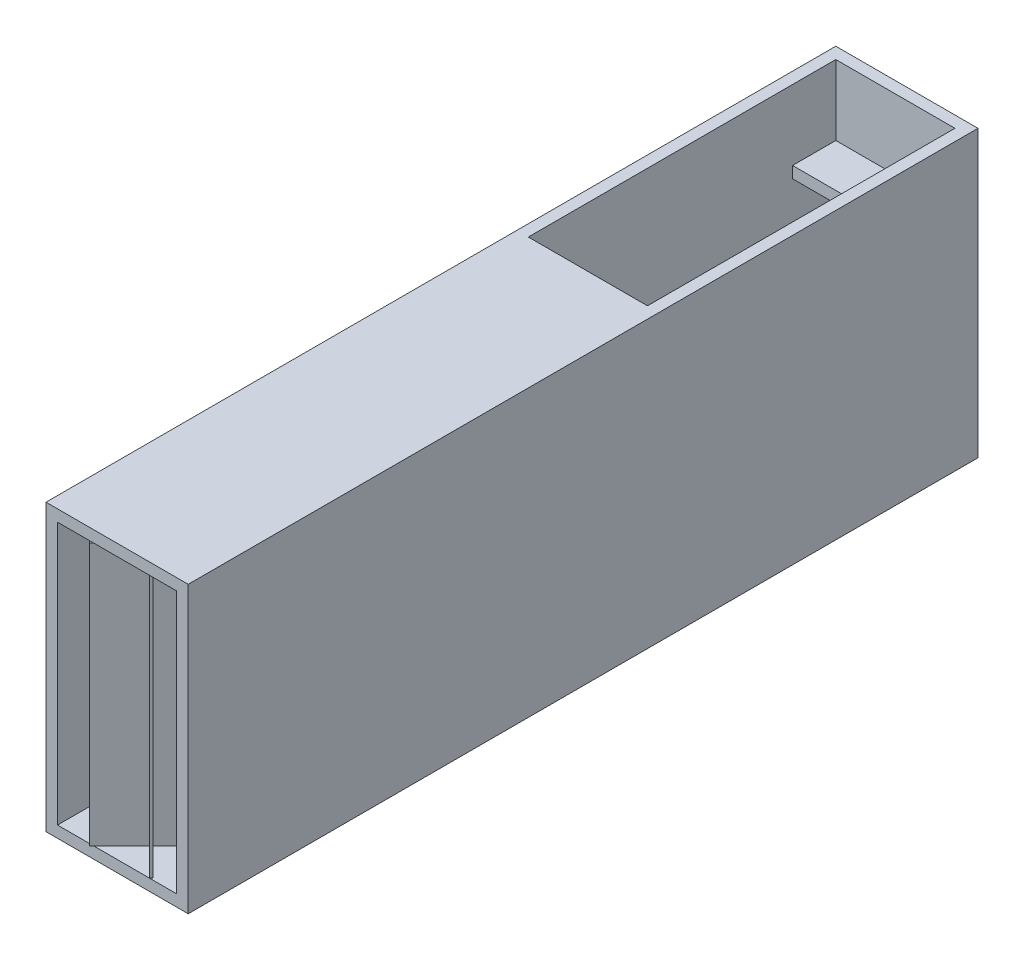
SolidWorks part; units mm, degrees
material "ABS"
ref_plane "Front Plane" through (0, 0, 0) normal (0, 0, 1) x (1, 0, 0)
ref_plane "Top Plane" through (0, 0, 0) normal (0, 1, 0) x (1, 0, 0)
ref_plane "Right Plane" through (0, 0, 0) normal (1, 0, 0) x (0, 0, -1)
sketch "Sketch1" plane through (0, 0, 0) normal (1, 0, 0) x (0, 0, -1)
  line L0 (-20.5, 9.4123) -> (-20.5, -21.7853) construction
  line L1 (-16.5, -15.0877) -> (-55.1183, -15.0877) construction
  line L2 (-16.5, 9.4123) -> (-57.9468, 9.4123) construction
ref_plane "Plane1" through (0, 0, 16) normal (0, 0, -1) x (-1, 0, 0)
sketch "Sketch2" plane through (0, 0, 16) normal (0, 0, -1) x (-1, 0, 0)
  line L2 (10.6894, -19.0877) -> (-1.7106, -19.0877)
  line L3 (10.4894, -15.0877) -> (-1.5106, -15.0877) construction
  line L4 (-1.7106, 9.4123) -> (10.6894, 9.4123)
  line L5 (-1.0106, -15.0877) -> (1.9894, -15.0877) construction
  line L7 (11.8894, 9.4123) -> (11.8894, -20.2877)
  line L8 (11.8894, -20.2877) -> (-2.9106, -20.2877)
  line L9 (-2.9106, -20.2877) -> (-2.9106, 9.4123)
  line L11 (-2.9106, 9.4123) -> (-1.7106, 9.4123)
  line L12 (-1.7106, 8.2123) -> (-1.7106, -19.0877)
  line L13 (11.8894, 9.4123) -> (10.6894, 9.4123)
  line L14 (10.6894, 8.2123) -> (10.6894, -19.0877)
  line L15 (-1.5106, -14.0877) -> (-1.5106, 2.1123) construction
  line L16 (10.4894, 2.1123) -> (10.4894, -14.0877) construction
  line L17 (-1.0106, 9.4123) -> (-1.5106, 9.4123) construction
  line L18 (10.4894, 9.4123) -> (9.9894, 9.4123) construction
  line L19 (-1.7106, 8.2123) -> (10.6894, 8.2123)
  dimension "D1" = 4
  dimension "D2" = 0.2
  dimension "D3" = 0.2
  dimension "D4" = 1.2
  dimension "D5" = 1.2
  dimension "D6" = 1.2
  dimension "D7" = 1.2
  dimension "D8" = 29.7
  dimension "D9" = 14.8
extrude "Boss-Extrude1" add sketch "Sketch2" against normal blind 81
ref_plane "Plane2" through (0, 0, 20.5) normal (0, 0, -1) x (-1, 0, 0)
sketch "Sketch3" plane through (0, 0, 20.5) normal (0, 0, -1) x (-1, 0, 0)
  line L0 (-1.5106, 2.1123) -> (10.4894, 2.1123) construction
  line L2 (-1.5106, 2.1123) -> (-1.0106, 2.1123) construction
  line L4 (9.9894, 2.1123) -> (10.4894, 2.1123) construction
  line L6 (10.4894, 0.9123) -> (-1.5106, 0.9123) construction
  line L15 (10.6894, 8.2123) -> (10.6894, -19.0877) construction
  line L16 (10.6894, 2.1123) -> (-1.7106, 2.1123)
  line L17 (10.6894, 2.1123) -> (10.6894, 0.9123)
  line L18 (10.6894, 0.9123) -> (-1.7106, 0.9123)
  line L19 (-1.7106, 2.1123) -> (-1.7106, 0.9123)
  line L20 (-1.7106, -19.0877) -> (-1.7106, 8.2123) construction
  line L21 (-1.0106, 4.1123) -> (9.9894, 4.1123) construction
  dimension "D1" = 1.2
  dimension "D2" = 1.2
  dimension "D3" = 2
extrude "Boss-Extrude2" add sketch "Sketch3" along normal blind 4.5
ref_plane "Plane3" through (0, 0, 43.5) normal (0, 0, 1) x (1, 0, 0)
sketch "Sketch6" plane through (0, 0, 43.5) normal (0, 0, 1) x (1, 0, 0)
  line L5 (-10.6894, 2.1123) -> (1.7106, 2.1123) construction
  line L6 (1.7106, 2.1123) -> (1.7106, 0.9123) construction
  line L7 (1.7106, 0.9123) -> (-10.6894, 0.9123) construction
  line L8 (-10.6894, 0.9123) -> (-10.6894, 2.1123) construction
  line L9 (-10.6894, 8.2123) -> (-10.6894, -19.0877) construction
  line L10 (-10.6894, 2.1123) -> (1.7106, 2.1123)
  line L11 (-10.6894, 2.1123) -> (-10.6894, 0.9123)
  line L12 (-10.6894, 0.9123) -> (1.7106, 0.9123)
  line L13 (1.7106, 2.1123) -> (1.7106, 0.9123)
  line L14 (1.7106, -19.0877) -> (1.7106, 8.2123) construction
extrude "Boss-Extrude3" add sketch "Sketch6" along normal blind 4.5
sketch "Sketch7" plane through (0, 2.1123, 0) normal (0, 1, 0) x (1, 0, 0)
  circle A1 centre (-4.4894, -46.25) radius 1
extrude "Cut-Extrude2" cut sketch "Sketch7" against normal blind 4.5
sketch "Sketch9" plane through (0, 2.1123, 0) normal (0, 1, 0) x (1, 0, 0)
  circle A0 centre (-4.4894, -17.75) radius 1
  dimension "D1" = 2
extrude "Cut-Extrude3" cut sketch "Sketch9" against normal blind 1.2
sketch "Sketch11" plane through (0, 9.4123, 0) normal (0, 1, 0) x (1, 0, 0)
  line L0 (-10.6894, -16) -> (-10.6894, -48)
  line L1 (-11.8894, -16) -> (2.9106, -16) construction
  line L2 (-10.6894, -48) -> (1.7106, -48)
  line L3 (1.7106, -48) -> (1.7106, -16)
  line L4 (-10.6894, -16) -> (1.7106, -16)
  line L5 (-11.8894, -97) -> (-11.8894, -16) construction
  line L8 (2.9106, -97) -> (2.9106, -16) construction
  dimension "D1" = 1.2
  dimension "D2" = 1.2
  dimension "D3" = 32
extrude "Cut-Extrude4" cut sketch "Sketch11" against normal blind 2
sketch "Sketch12" plane through (0, -20.2877, 0) normal (0, -1, 0) x (1, 0, 0)
  line L0 (-11.8894, 97) -> (-11.8894, 16) construction
  line L1 (-10.6894, 16) -> (1.7106, 16) construction
  circle A0 centre (-4.4894, 27) radius 1.5
  dimension "D1" = 3
  dimension "D2" = 7.4
  dimension "D3" = 11
extrude "Cut-Extrude5" cut sketch "Sketch12" against normal blind 3
sketch "Sketch13" plane through (0, 0, 16) normal (0, 0, -1) x (-1, 0, 0)
  line L1 (-2.9106, -20.2877) -> (11.8894, -20.2877)
  line L2 (-2.9106, -20.2877) -> (-2.9106, 9.4123)
  line L3 (-2.9106, 9.4123) -> (11.8894, 9.4123)
  line L4 (11.8894, -20.2877) -> (11.8894, 9.4123)
extrude "Boss-Extrude4" add sketch "Sketch13" along normal blind 1.2
sketch "Sketch14" plane through (0, 8.2123, 0) normal (0, -1, 0) x (1, 0, 0)
  line L0 (-11.186, 48.6499) -> (2.4509, 62.2868)
  line L2 (-10.6894, 97) -> (-10.6894, 48) construction
  line L3 (1.7106, 97) -> (1.7106, 48) construction
  line L4 (2.4509, 48.896) -> (-11.2459, 62.5928)
  line L5 (-11.186, 58.2267) -> (2.4509, 71.8636)
  line L6 (2.4509, 58.4728) -> (-11.2459, 72.1696)
  line L7 (-11.186, 67.8035) -> (2.4509, 81.4404)
  line L8 (2.4509, 68.0497) -> (-11.2459, 81.7464)
  line L9 (-11.186, 77.3803) -> (2.4509, 91.0172)
  line L10 (2.4509, 77.6265) -> (-11.2459, 91.3233)
  line L11 (-10.8201, 87.3231) -> (-1.1432, 97)
  line L12 (1.7106, 87.9435) -> (-7.3458, 97)
  line L13 (-10.6894, 97) -> (1.7106, 97) construction
  line L14 (-10.6894, 97) -> (1.7106, 97) construction
  dimension "D1" = 45
  dimension "D2" = 90
  dimension "D3" = 5
extrude "Extrude-Thin4" add sketch "Sketch14" along normal up to surface (27.3 mm away) thin
